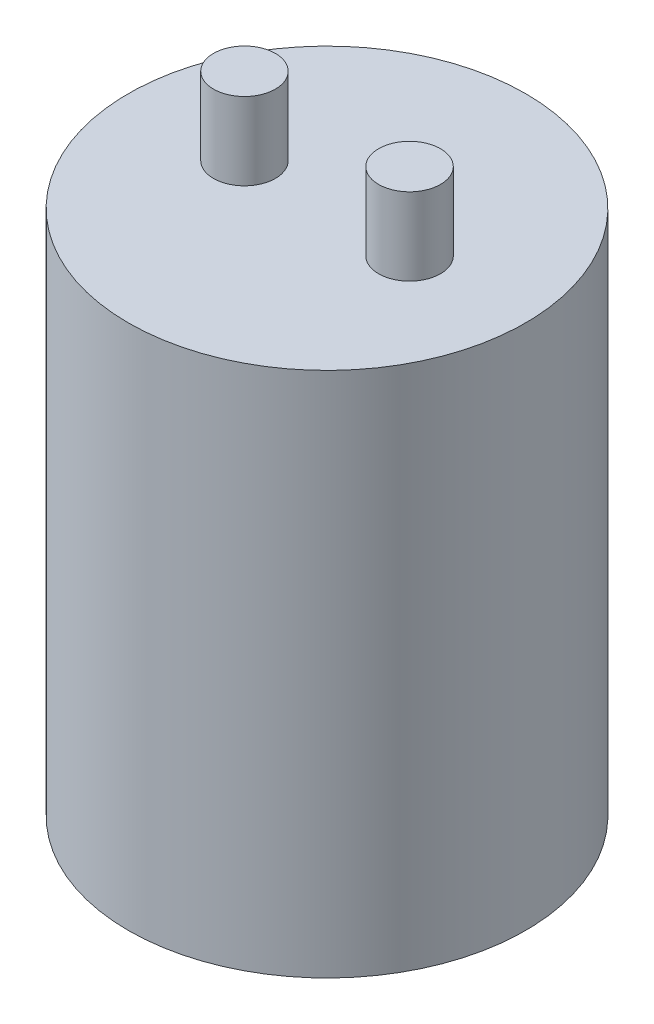
SolidWorks part; units mm, degrees
ref_plane "前视基准面" through (0, 0, 0) normal (0, 0, 1) x (1, 0, 0)
ref_plane "上视基准面" through (0, 0, 0) normal (0, 1, 0) x (1, 0, 0)
ref_plane "右视基准面" through (0, 0, 0) normal (1, 0, 0) x (0, 0, -1)
sketch "草图1" plane through (0, 0, 0) normal (0, 1, 0) x (1, 0, 0)
  circle A0 centre (0, 0) radius 38.5
  dimension "D1" = 77
extrude "凸台-拉伸1" add sketch "草图1" along normal mid plane 102
sketch "草图2" plane through (0, 51, 0) normal (0, 1, 0) x (1, 0, 0)
  line L0 (0, 0) -> (0, 28.7891) construction
  circle A0 centre (16, 0) radius 6
  circle A1 centre (-16, 0) radius 6
  dimension "D1" = 12
  dimension "D2" = 32
extrude "凸台-拉伸2" add sketch "草图2" along normal blind 15
